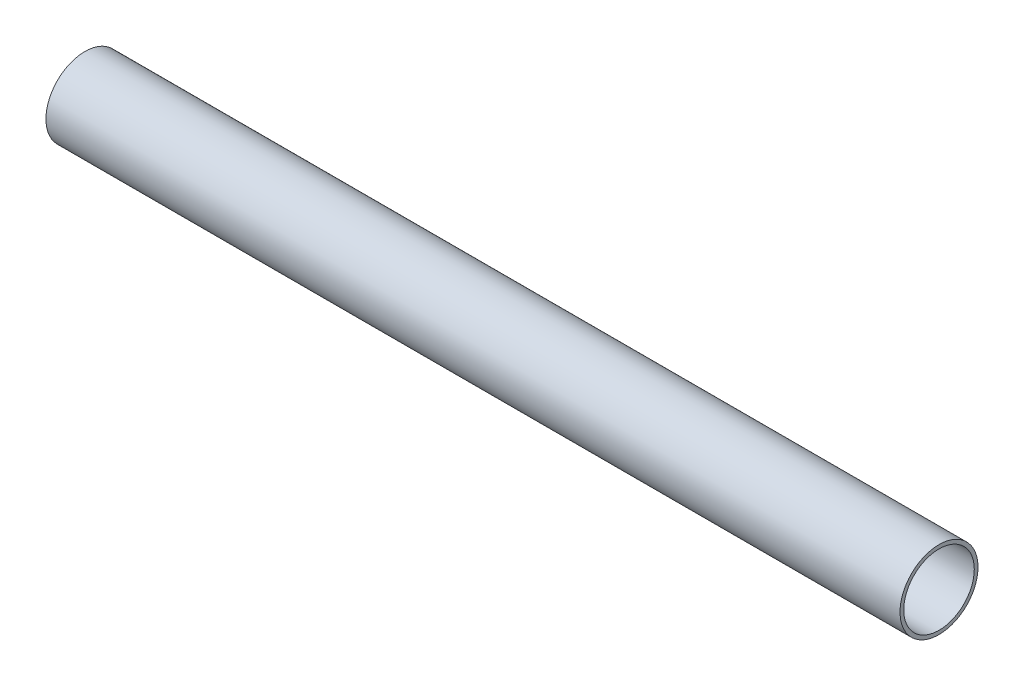
SolidWorks part; units mm, degrees
material "PTFE (allgemein)"
ref_plane "Ebene vorne" through (0, 0, 0) normal (0, 0, 1) x (1, 0, 0)
ref_plane "Ebene oben" through (0, 0, 0) normal (0, 1, 0) x (1, 0, 0)
ref_plane "Ebene rechts" through (0, 0, 0) normal (1, 0, 0) x (0, 0, -1)
sketch "Skizze1" plane through (0, 0, 0) normal (1, 0, 0) x (0, 0, -1)
  circle A0 centre (0, 0) radius 9.5
  circle A1 centre (0, 0) radius 10.5
  dimension "D1" = 19
  dimension "D2" = 21
extrude "Aufsatz-Linear austragen1" add sketch "Skizze1" along normal blind 230
